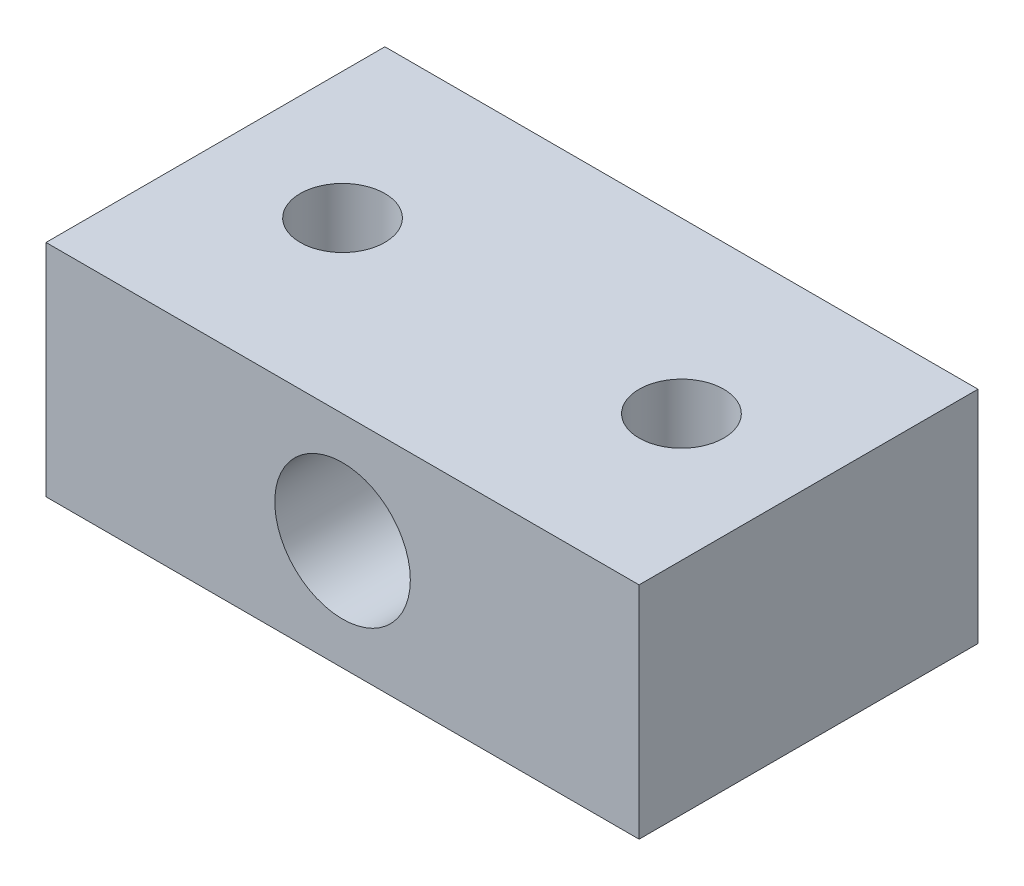
SolidWorks part; units mm, degrees
ref_plane "Front Plane" through (0, 0, 0) normal (0, 0, 1) x (1, 0, 0)
ref_plane "Top Plane" through (0, 0, 0) normal (0, 1, 0) x (1, 0, 0)
ref_plane "Right Plane" through (0, 0, 0) normal (1, 0, 0) x (0, 0, -1)
sketch "Sketch1" plane through (0, 0, 0) normal (0, 1, 0) x (1, 0, 0)
  line L1 (-17.5, 10) -> (17.5, 10)
  line L2 (-17.5, 10) -> (-17.5, -10)
  line L3 (-17.5, -10) -> (17.5, -10)
  line L4 (17.5, 10) -> (17.5, -10)
  line L5 (-17.5, 10) -> (17.5, -10) construction
  line L6 (-17.5, -10) -> (17.5, 10) construction
  circle A0 centre (-10, 0) radius 2.5
  circle A1 centre (10, 0) radius 2.5
  point P0 (0, 0)
  dimension "D5" = 5
  dimension "D1" = 20
  dimension "D2" = 35
  dimension "D3" = 7.5
  dimension "D4" = 10
  dimension "D6" = 10
  dimension "D7" = 7.5
extrude "Boss-Extrude1" add sketch "Sketch1" along normal blind 13
sketch "Sketch2" plane through (0, 0, 10) normal (0, 0, 1) x (1, 0, 0)
  line L0 (-17.5, 0) -> (17.5, 0) construction
  line L1 (-17.5, 13) -> (-17.5, 0) construction
  circle A0 centre (0, 6.5) radius 4
  point P6 (-1.7894, 2.447)
  dimension "D3" = 8
  dimension "D1" = 6.5
  dimension "D2" = 17.5
extrude "Cut-Extrude1" cut sketch "Sketch2" against normal through all
